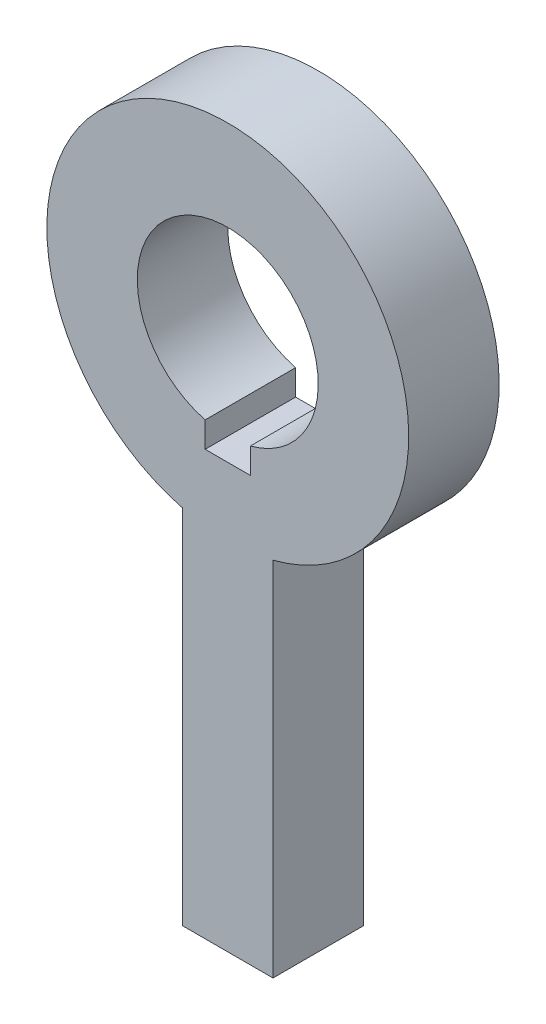
SolidWorks part; units mm, degrees
ref_plane "Front Plane" through (0, 0, 0) normal (0, 0, 1) x (1, 0, 0)
ref_plane "Top Plane" through (0, 0, 0) normal (0, 1, 0) x (1, 0, 0)
ref_plane "Right Plane" through (0, 0, 0) normal (1, 0, 0) x (0, 0, -1)
sketch "Sketch1" plane through (0, 0, 0) normal (0, 0, 1) x (1, 0, 0)
  line L0 (0, 0) -> (0, -92.4239) construction
  line L1 (0, 0) -> (0, -10) construction
  line L2 (-5, -59.3649) -> (5, -59.3649)
  line L3 (-5, -59.3649) -> (-5, -19.3649)
  line L5 (5, -59.3649) -> (5, -19.3649)
  line L6 (-5, -59.3649) -> (5, -19.3649) construction
  line L7 (-5, -19.3649) -> (5, -59.3649) construction
  line L15 (-2.5, -12.5) -> (2.5, -12.5)
  line L16 (-2.5, -12.5) -> (-2.5, -9.6825)
  line L18 (2.5, -12.5) -> (2.5, -9.6825)
  line L19 (-2.5, -12.5) -> (0, -10) construction
  line L20 (0, -10) -> (2.5, -12.5) construction
  arc A1 (5, -19.3649) -> (-5, -19.3649) centre (0, 0) ccw
  arc A2 (2.5, -9.6825) -> (-2.5, -9.6825) centre (0, 0) ccw
  point P3 (0, -21.3624)
  point P4 (0, -39.3649)
  dimension "D1" = 20
  dimension "D2" = 40
  dimension "D5" = 2.5
  dimension "D3" = 40
  dimension "D4" = 10
  dimension "D6" = 5
extrude "Boss-Extrude1" add sketch "Sketch1" along normal blind 10
